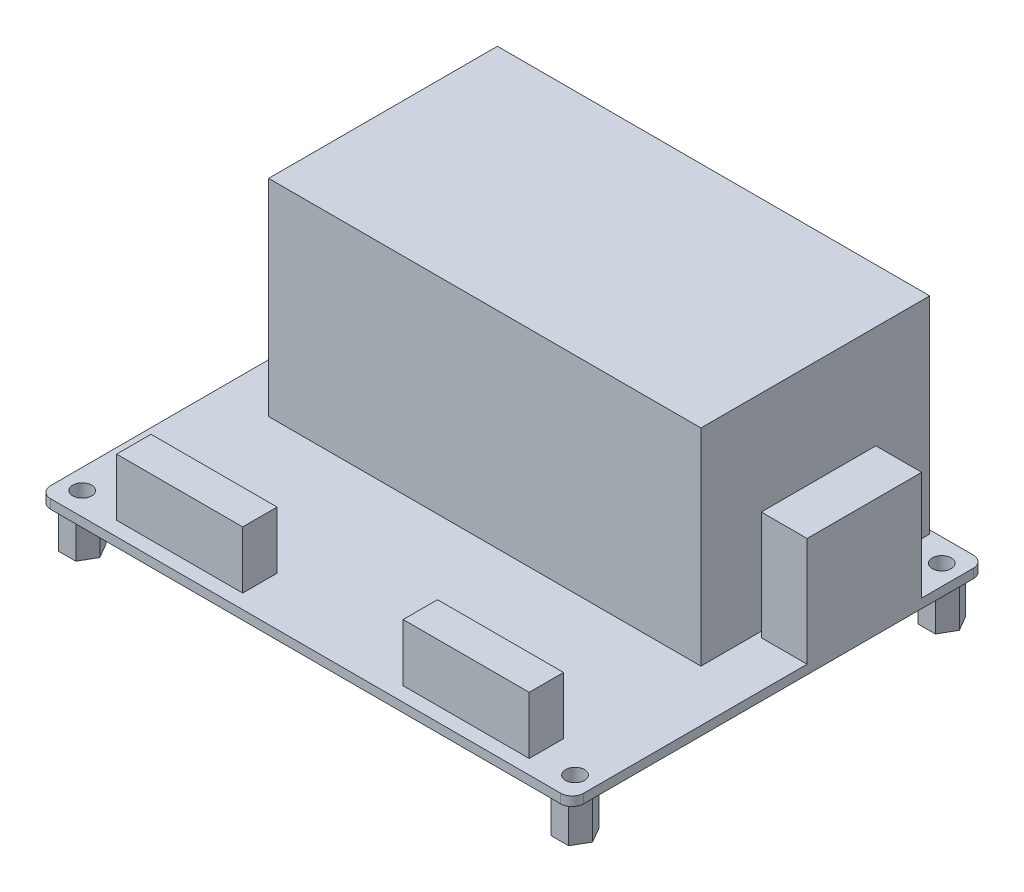
SolidWorks part; units mm, degrees
ref_plane "前视基准面" through (0, 0, 0) normal (0, 0, 1) x (1, 0, 0)
ref_plane "上视基准面" through (0, 0, 0) normal (0, 1, 0) x (1, 0, 0)
ref_plane "右视基准面" through (0, 0, 0) normal (1, 0, 0) x (0, 0, -1)
sketch "草图1" plane through (0, 0, 0) normal (0, 1, 0) x (1, 0, 0)
  line L1 (-44.5, -36) -> (44.5, -36)
  line L2 (-46.5, -34) -> (-46.5, 34)
  line L3 (-44.5, 36) -> (44.5, 36)
  line L4 (46.5, -34) -> (46.5, 34)
  line L5 (-46.5, -36) -> (46.5, 36) construction
  line L6 (-46.5, 36) -> (46.5, -36) construction
  line L7 (-43, -32) -> (43, -32) construction
  line L8 (-43, -32) -> (-43, 32) construction
  line L9 (-43, 32) -> (43, 32) construction
  line L10 (43, -32) -> (43, 32) construction
  line L11 (-43, -32) -> (43, 32) construction
  line L12 (-43, 32) -> (43, -32) construction
  arc A0 (-44.5, -36) -> (-46.5, -34) centre (-44.5, -34) cw
  arc A1 (44.5, -36) -> (46.5, -34) centre (44.5, -34) ccw
  arc A2 (44.5, 36) -> (46.5, 34) centre (44.5, 34) cw
  arc A3 (-46.5, 34) -> (-44.5, 36) centre (-44.5, 34) cw
  circle A4 centre (-43, 32) radius 1.65
  circle A5 centre (43, 32) radius 1.65
  circle A6 centre (43, -32) radius 1.65
  circle A7 centre (-43, -32) radius 1.65
  point P0 (0, 0)
  point P18 (0, 0)
  dimension "D3" = 2
  dimension "D4" = 3.3
  dimension "D1" = 93
  dimension "D2" = 72
  dimension "D5" = 86
  dimension "D6" = 64
extrude "凸台-拉伸1" add sketch "草图1" along normal blind 1.6
sketch "草图2" plane through (0, 1.6, 0) normal (0, 1, 0) x (1, 0, 0)
  line L5 (-46.5, 34) -> (-46.5, -34) construction
  line L10 (46.5, -34) -> (46.5, 34) construction
  line L15 (-44.5, -36) -> (44.5, -36) construction
  line L16 (-35.5, -27.5) -> (-13.5, -27.5)
  line L17 (-35.5, -27.5) -> (-35.5, -33.5)
  line L18 (-35.5, -33.5) -> (-13.5, -33.5)
  line L19 (-13.5, -27.5) -> (-13.5, -33.5)
  line L20 (14.5, -27.5) -> (36.5, -27.5)
  line L21 (14.5, -27.5) -> (14.5, -33.5)
  line L22 (14.5, -33.5) -> (36.5, -33.5)
  line L23 (36.5, -27.5) -> (36.5, -33.5)
  dimension "D1" = 11
  dimension "D2" = 10
  dimension "D3" = 22
  dimension "D4" = 2.5
  dimension "D5" = 6
extrude "凸台-拉伸2" add sketch "草图2" along normal blind 10
sketch "草图3" plane through (0, 1.6, 0) normal (0, 1, 0) x (1, 0, 0)
  line L1 (-37.9153, 35.3716) -> (37.5313, 35.3716)
  line L2 (-37.9153, 35.3716) -> (-37.9153, -4.5594)
  line L3 (-37.9153, -4.5594) -> (37.5313, -4.5594)
  line L4 (37.5313, 35.3716) -> (37.5313, -4.5594)
extrude "凸台-拉伸3" add sketch "草图3" along normal blind 36
sketch "草图4" plane through (0, 1.6, 0) normal (0, 1, 0) x (1, 0, 0)
  line L0 (-46.5, 34) -> (-46.5, -34) construction
  line L1 (-46.5, 25) -> (-38.5, 25)
  line L2 (-46.5, 25) -> (-46.5, 5)
  line L3 (-46.5, 5) -> (-38.5, 5)
  line L4 (-38.5, 25) -> (-38.5, 5)
  line L5 (46.5, -34) -> (46.5, 34) construction
  line L6 (46.5, 25) -> (38.5, 25)
  line L7 (46.5, 25) -> (46.5, 5)
  line L8 (46.5, 5) -> (38.5, 5)
  line L9 (38.5, 25) -> (38.5, 5)
  line L10 (44.5, 36) -> (-44.5, 36) construction
  dimension "D1" = 11
  dimension "D2" = 20
  dimension "D3" = 8
extrude "凸台-拉伸4" add sketch "草图4" along normal blind 19
sketch "草图5" plane through (0, 0, 0) normal (0, -1, 0) x (1, 0, 0)
  line L1 (39.94, -32) -> (41.47, -34.65)
  line L2 (41.47, -34.65) -> (44.53, -34.65)
  line L3 (44.53, -34.65) -> (46.06, -32)
  line L4 (46.06, -32) -> (44.53, -29.35)
  line L5 (44.53, -29.35) -> (41.47, -29.35)
  line L6 (41.47, -29.35) -> (39.94, -32)
  line L7 (-39.94, -32) -> (-41.47, -29.35)
  line L8 (-41.47, -29.35) -> (-44.53, -29.35)
  line L9 (-44.53, -29.35) -> (-46.06, -32)
  line L10 (-46.06, -32) -> (-44.53, -34.65)
  line L11 (-44.53, -34.65) -> (-41.47, -34.65)
  line L12 (-41.47, -34.65) -> (-39.94, -32)
  line L13 (-39.94, 32) -> (-41.47, 34.65)
  line L14 (-41.47, 34.65) -> (-44.53, 34.65)
  line L15 (-44.53, 34.65) -> (-46.06, 32)
  line L16 (-46.06, 32) -> (-44.53, 29.35)
  line L17 (-44.53, 29.35) -> (-41.47, 29.35)
  line L18 (-41.47, 29.35) -> (-39.94, 32)
  line L19 (39.94, 32) -> (41.47, 29.35)
  line L20 (41.47, 29.35) -> (44.53, 29.35)
  line L21 (44.53, 29.35) -> (46.06, 32)
  line L22 (46.06, 32) -> (44.53, 34.65)
  line L23 (44.53, 34.65) -> (41.47, 34.65)
  line L24 (41.47, 34.65) -> (39.94, 32)
  circle A0 centre (43, -32) radius 1.65
  circle A2 centre (-43, -32) radius 1.65
  circle A4 centre (-43, 32) radius 1.65
  circle A6 centre (43, 32) radius 1.65
  circle A8 centre (43, -32) radius 2.65 construction
  circle A9 centre (-43, -32) radius 2.65 construction
  circle A10 centre (-43, 32) radius 2.65 construction
  circle A11 centre (43, 32) radius 2.65 construction
  dimension "D1" = 5.3
extrude "凸台-拉伸5" add sketch "草图5" along normal blind 7
